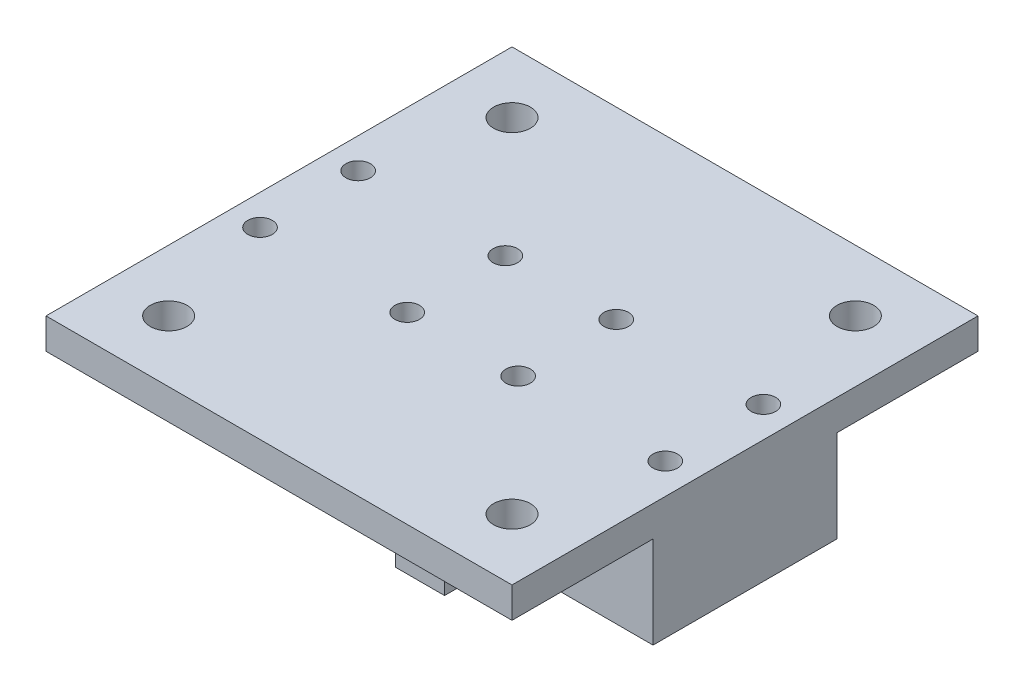
SolidWorks part; units mm, degrees
ref_plane "Front Plane" through (0, 0, 0) normal (0, 0, 1) x (1, 0, 0)
ref_plane "Top Plane" through (0, 0, 0) normal (0, 1, 0) x (1, 0, 0)
ref_plane "Right Plane" through (0, 0, 0) normal (1, 0, 0) x (0, 0, -1)
sketch "Sketch1" plane through (0, 0, 0) normal (0, 0, 1) x (1, 0, 0)
  line L1 (-2.5, -5) -> (2.5, -5)
  line L2 (0, 15) -> (38, 15)
  line L3 (0, 15) -> (-38, 15)
  line L4 (-38, 15) -> (-38, 10)
  line L6 (38, 10) -> (38, 15)
  line L7 (-38, 10) -> (-38, -5)
  line L8 (-38, -5) -> (-4, -5)
  line L9 (38, 10) -> (38, -5)
  line L10 (4, -5) -> (4, -15)
  line L11 (4, -15) -> (0, -15)
  line L12 (-4, -5) -> (-4, -15)
  line L13 (-4, -15) -> (0, -15)
  line L14 (4, -5) -> (38, -5)
  line L15 (0, -10) -> (2.5, -10)
  line L16 (2.5, -7.5) -> (2.5, -10)
  line L17 (2.5, -7.5) -> (2.5, -5)
  line L18 (0, -10) -> (-2.5, -10)
  line L19 (-2.5, -7.5) -> (-2.5, -10)
  line L20 (-2.5, -7.5) -> (-2.5, -5)
  dimension "D3" = 38
  dimension "D4" = 38
  dimension "D5" = 5
  dimension "D6" = 15
  dimension "D7" = 5
extrude "Boss-Extrude1" add sketch "Sketch1" against normal blind 30
ref_plane "Plane1" through (0, 0, 0) normal (0, 0, 1) x (1, 0, 0)
sketch "Sketch2" plane through (0, 0, 0) normal (0, 0, 1) x (1, 0, 0)
  line L0 (-38, 15) -> (-38, 10)
  line L1 (-38, 15) -> (-38, -5) construction
  line L2 (-38, 10) -> (38, 10)
  line L3 (38, -5) -> (38, 15) construction
  line L4 (38, 10) -> (38, 15)
  line L5 (38, 15) -> (-38, 15)
  dimension "D1" = 5
extrude "Boss-Extrude2" add sketch "Sketch2" along normal blind 23
ref_plane "Plane2" through (0, 0, -30) normal (0, 0, -1) x (-1, 0, 0)
sketch "Sketch3" plane through (0, 0, -30) normal (0, 0, -1) x (-1, 0, 0)
  line L0 (-38, 15) -> (-38, 10)
  line L1 (-38, -5) -> (-38, 15) construction
  line L2 (-38, 10) -> (38, 10)
  line L3 (38, 15) -> (38, -5) construction
  line L4 (38, 10) -> (38, 15)
  line L5 (38, 15) -> (-38, 15)
  dimension "D1" = 5
extrude "Boss-Extrude3" add sketch "Sketch3" along normal blind 23
ref_plane "Plane3" through (0, -15, 0) normal (0, -1, 0) x (-1, 0, 0)
sketch "Sketch4" plane through (0, -15, 0) normal (0, -1, 0) x (-1, 0, 0)
  line L1 (-4, 30) -> (-4, 0) construction
  line L2 (-4, 5) -> (4, 5)
  line L3 (4, 30) -> (4, 0) construction
  line L6 (-4, 25) -> (4, 25)
  line L10 (-4, 5) -> (-4, 25)
  line L11 (4, 5) -> (4, 25)
extrude "Cut-Extrude1" cut sketch "Sketch4" against normal blind 5
ref_plane "Plane4" through (0, -5, 0) normal (0, -1, 0) x (-1, 0, 0)
sketch "Sketch5" plane through (0, -5, 0) normal (0, -1, 0) x (-1, 0, 0)
  circle A4 centre (33.0482, 6.9546) radius 2
  circle A5 centre (9.0482, 6.9546) radius 2
  circle A6 centre (33.0482, 22.9546) radius 2
  circle A7 centre (9.0482, 22.9546) radius 2
  circle A8 centre (-9, 7) radius 2
  circle A9 centre (-33, 7) radius 2
  circle A10 centre (-33, 23) radius 2
  circle A12 centre (-9, 23) radius 2
  dimension "D6" = 4
extrude "Cut-Extrude2" cut sketch "Sketch5" against normal blind 20
ref_plane "Plane5" through (0, 15, 0) normal (0, 1, 0) x (1, 0, 0)
sketch "Sketch6" plane through (0, 15, 0) normal (0, 1, 0) x (1, 0, 0)
  circle A2 centre (28, -13) radius 3
  circle A4 centre (-28, -13) radius 3
  circle A6 centre (-28, 43) radius 3
  circle A8 centre (28, 43) radius 3
  dimension "D1" = 6
extrude "Cut-Extrude3" cut sketch "Sketch6" against normal blind 5
